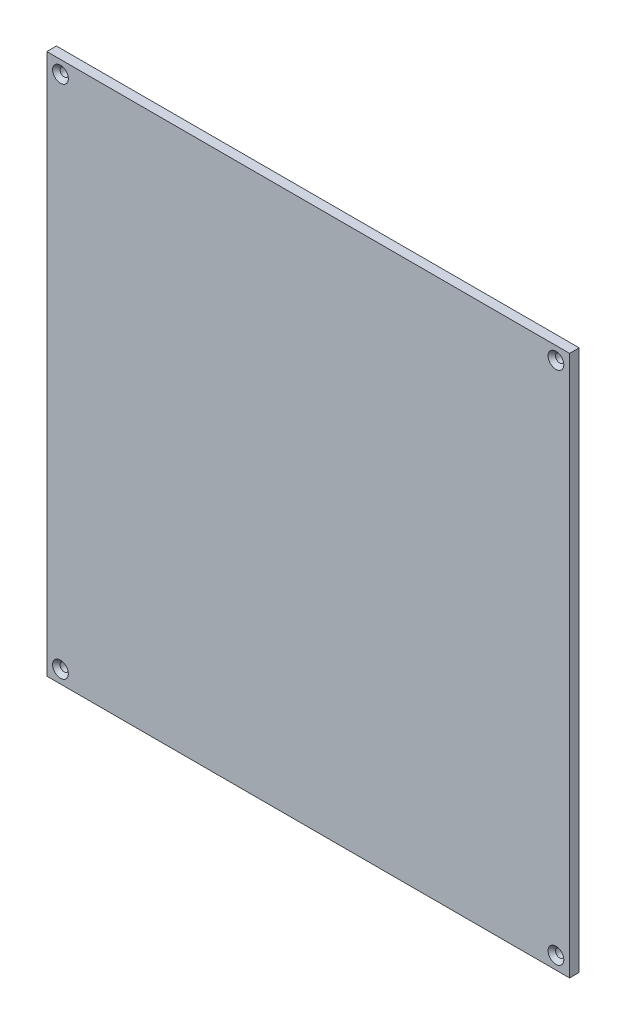
SolidWorks part; units mm, degrees
ref_plane "Front Plane" through (0, 0, 0) normal (0, 0, 1) x (1, 0, 0)
ref_plane "Top Plane" through (0, 0, 0) normal (0, 1, 0) x (1, 0, 0)
ref_plane "Right Plane" through (0, 0, 0) normal (1, 0, 0) x (0, 0, -1)
sketch "Model" plane through (0, 0, 0) normal (0, 0, 1) x (1, 0, 0)
  line L0 (-173, 179) -> (173, 179)
  line L1 (-173, -179) -> (173, -179)
  line L7 (-173, -179) -> (-173, 179)
  line L14 (173, 0) -> (-173, 0) construction
  line L18 (0, 179) -> (0, -179) construction
  line L23 (173, 179) -> (173, -179)
  point P1 (0, 0)
  dimension "D1" = 358
  dimension "D2" = 346
extrude "Boss-Extrude1" add sketch "Model" along normal blind 6.35
sketch "Sketch2" plane through (0, 0, 6.35) normal (0, 0, 1) x (1, 0, 0)
  line L0 (173, 0) -> (-173, 0) construction
  line L1 (173, 179) -> (173, -179) construction
  line L2 (-173, -179) -> (-173, 179) construction
  line L3 (0, 179) -> (0, -179) construction
  line L6 (-173, 179) -> (173, 179) construction
  line L7 (-173, -179) -> (173, -179) construction
  circle A0 centre (-163.95, 170.5) radius 2.55
  circle A1 centre (163.95, 170.5) radius 2.55
  circle A2 centre (163.95, -170.5) radius 2.55
  circle A3 centre (-163.95, -170.5) radius 2.55
  dimension "D1" = 5.1
  dimension "D3" = 341
  dimension "D2" = 327.9
extrude "Cut-Extrude1" cut sketch "Sketch2" against normal up to next contours A0 | A3 | A2 | A1
hole_wizard "CSK for M5 Flat Head Machine Screw1" positions "Sketch3" profile "Sketch4" countersink size "M5" standard "ANSI Metric" end condition through all
sketch "Sketch3" plane through (0, 0, 6.35) normal (0, 0, 1) x (1, 0, 0)
  point P0 (-163.95, 170.5)
  point P3 (163.95, 170.5)
  point P6 (163.95, -170.5)
  point P9 (-163.95, -170.5)
sketch "Sketch4" plane through (-163.95, 170.5, 6.35) normal (1, 0, 0) x (0, -1, 0)
  line L0 (0, 0) -> (0, 6.35)
  line L1 (0, 6.35) -> (2.75, 6.35)
  line L2 (2.75, 6.35) -> (2.75, 2.45)
  line L3 (2.75, 2.45) -> (5.2, 0)
  line L5 (5.2, 0) -> (0, 0)
  line L6 (-2.75, 2.45) -> (-5.2, 0) construction
  line L11 (0, -6.35) -> (0, 107.95) construction
  dimension "Thru Hole Dia." = 5.5
  dimension "Thru Hole Depth" = 6.35
  dimension "Near C'Sink Dia." = 10.4
  dimension "Near C'Sink Angle" = 90
